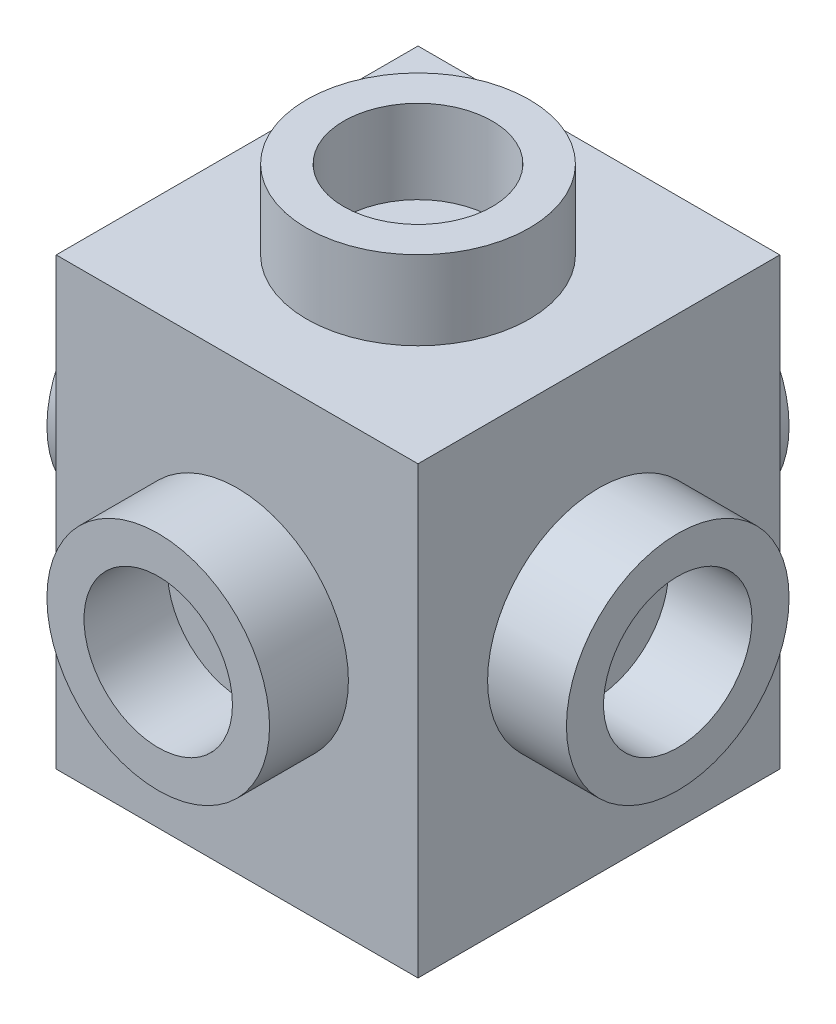
SolidWorks part; units mm, degrees
ref_plane "Спереди" through (0, 0, 0) normal (0, 0, 1) x (1, 0, 0)
ref_plane "Сверху" through (0, 0, 0) normal (0, 1, 0) x (1, 0, 0)
ref_plane "Справа" through (0, 0, 0) normal (1, 0, 0) x (0, 0, -1)
sketch "Эскиз1" plane through (0, 0, 0) normal (0, 1, 0) x (1, 0, 0)
  line L1 (3.9, -3.9) -> (-3.9, -3.9)
  line L2 (3.9, -3.9) -> (3.9, 3.9)
  line L3 (3.9, 3.9) -> (-3.9, 3.9)
  line L4 (-3.9, -3.9) -> (-3.9, 3.9)
  line L5 (3.9, -3.9) -> (-3.9, 3.9) construction
  line L6 (3.9, 3.9) -> (-3.9, -3.9) construction
  point P0 (0, 0)
  dimension "D1" = 7.8
  dimension "D2" = 7.8
extrude "Бобышка-Вытянуть1" add sketch "Эскиз1" along normal blind 9.6
sketch "Эскиз2" plane through (0, 9.6, 0) normal (0, 1, 0) x (1, 0, 0)
  circle A0 centre (0, 0) radius 2.4
extrude "Бобышка-Вытянуть2" add sketch "Эскиз2" along normal blind 1.7
sketch "Эскиз6" plane through (0, 0, 3.9) normal (0, 0, 1) x (1, 0, 0)
  line L0 (-3.9, 9.6) -> (3.9, 0)
  line L1 (3.9, 9.6) -> (-3.9, 0)
  circle A0 centre (0, 4.8) radius 2.4
extrude "Бобышка-Вытянуть6" add sketch "Эскиз6" along normal blind 1.7 contours L1 A0 L0 | L0 A0 L1 | L1 A0 L0 | L0 A0 L1
sketch "Эскиз7" plane through (3.9, 0, 0) normal (1, 0, 0) x (0, 0, -1)
  line L0 (-3.9, 9.6) -> (3.9, 0)
  line L1 (3.9, 9.6) -> (-3.9, 0)
  circle A0 centre (0, 4.8) radius 2.4
  point P10 (-11.6106, 3.3352)
extrude "Бобышка-Вытянуть7" add sketch "Эскиз7" along normal blind 1.7 contours L1 A0 L0 | L0 A0 L1 | L1 A0 L0 | L0 A0 L1
sketch "Эскиз9" plane through (0, 0, -3.9) normal (0, 0, -1) x (-1, 0, 0)
  line L0 (-3.9, 9.6) -> (3.9, 0)
  line L1 (3.9, 9.6) -> (-3.9, 0)
  circle A0 centre (0, 4.8) radius 2.4
extrude "Бобышка-Вытянуть8" add sketch "Эскиз9" along normal blind 1.7 contours L1 A0 L0 | L0 A0 L1 | L1 A0 L0 | L0 A0 L1
sketch "Эскиз10" plane through (-3.9, 0, 0) normal (-1, 0, 0) x (0, 0, 1)
  line L0 (-3.9, 9.6) -> (3.9, 0)
  line L1 (3.9, 9.6) -> (-3.9, 0)
  circle A0 centre (0, 4.8) radius 2.4
extrude "Бобышка-Вытянуть9" add sketch "Эскиз10" along normal blind 1.7 contours L1 A0 L0 | L0 A0 L1 | L1 A0 L0 | L0 A0 L1
sketch "Эскиз11" plane through (0, 0, 0) normal (0, -1, 0) x (1, 0, 0)
  line L0 (-3.9, 3.9) -> (3.9, -3.9)
  line L1 (3.9, 3.9) -> (-3.9, -3.9)
  circle A0 centre (0, 0) radius 2.5
extrude "Вырез-Вытянуть1" cut sketch "Эскиз11" against normal blind 1.8 contours L1 A0 L0 | L0 A0 L1 | L1 A0 L0 | L0 A0 L1
sketch "Эскиз12" plane through (0, 0, 5.6) normal (0, 0, 1) x (1, 0, 0)
  circle A0 centre (0, 4.8) radius 1.6
extrude "Вырез-Вытянуть2" cut sketch "Эскиз12" against normal blind 1.8
sketch "Эскиз13" plane through (-5.6, 0, 0) normal (-1, 0, 0) x (0, 0, 1)
  circle A0 centre (0, 4.8) radius 1.6
extrude "Вырез-Вытянуть3" cut sketch "Эскиз13" against normal blind 1.8
sketch "Эскиз14" plane through (0, 0, -5.6) normal (0, 0, -1) x (-1, 0, 0)
  circle A0 centre (0, 4.8) radius 1.6
extrude "Вырез-Вытянуть4" cut sketch "Эскиз14" against normal blind 1.8
sketch "Эскиз15" plane through (5.6, 0, 0) normal (1, 0, 0) x (0, 0, -1)
  circle A0 centre (0, 4.8) radius 1.6
extrude "Вырез-Вытянуть5" cut sketch "Эскиз15" against normal blind 1.8
sketch "Эскиз16" plane through (0, 11.3, 0) normal (0, 1, 0) x (1, 0, 0)
  circle A0 centre (0, 0) radius 1.6
extrude "Вырез-Вытянуть6" cut sketch "Эскиз16" against normal blind 1.8
